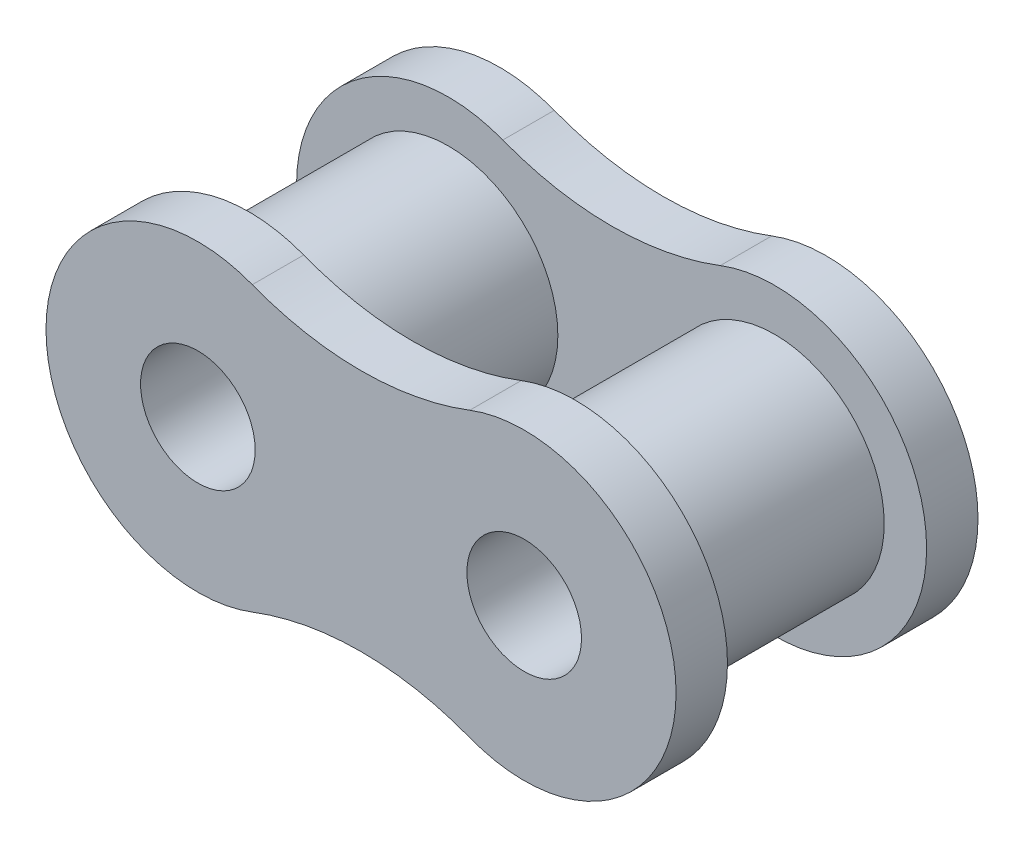
SolidWorks part; units mm, degrees
material "1.7033 (34Cr4)"
ref_plane "Спереди" through (0, 0, 0) normal (0, 0, 1) x (1, 0, 0)
ref_plane "Сверху" through (0, 0, 0) normal (0, 1, 0) x (1, 0, 0)
ref_plane "Справа" through (0, 0, 0) normal (1, 0, 0) x (0, 0, -1)
sketch "Эскиз1" plane through (0, 0, 0) normal (0, 0, 1) x (1, 0, 0)
  line L0 (-19.0259, 0) -> (6.7034, 0) construction
  line L1 (0, 3.4093) -> (0, -8.0834) construction
  circle A0 centre (-6.35, 0) radius 2.23
  circle A1 centre (6.35, 0) radius 2.23
  circle A2 centre (-6.35, 0) radius 4.26
  circle A3 centre (6.35, 0) radius 4.26
  dimension "D1" = 4.46
  dimension "D3" = 8.52
  dimension "D2" = 12.7
extrude "Бобышка-Вытянуть1" add sketch "Эскиз1" along normal mid plane 11.75
sketch "Эскиз2" plane through (0, 0, 0) normal (0, 0, 1) x (1, 0, 0)
  arc A0 (-4.2321, 5.5175) -> (-4.2321, -5.5175) centre (-6.35, 0) ccw
  arc A1 (4.2321, -5.5175) -> (4.2321, 5.5175) centre (6.35, 0) ccw
  arc A2 (-4.2321, 5.5175) -> (4.2321, 5.5175) centre (0, 16.5432) ccw
  arc A3 (4.2321, -5.5175) -> (-4.2321, -5.5175) centre (0, -16.5432) ccw
  circle A4 centre (-6.35, 0) radius 3
  circle A5 centre (6.35, 0) radius 3
  dimension "D1" = 11.82
  dimension "D2" = 23.62
  dimension "D3" = 6
extrude "Бобышка-Вытянуть2" add sketch "Эскиз2" against normal blind 2 from offset 5.875
mirror "Зеркальное отражение1" about plane through (0, 0, 0) normal (0, 0, 1) of "Бобышка-Вытянуть2"
